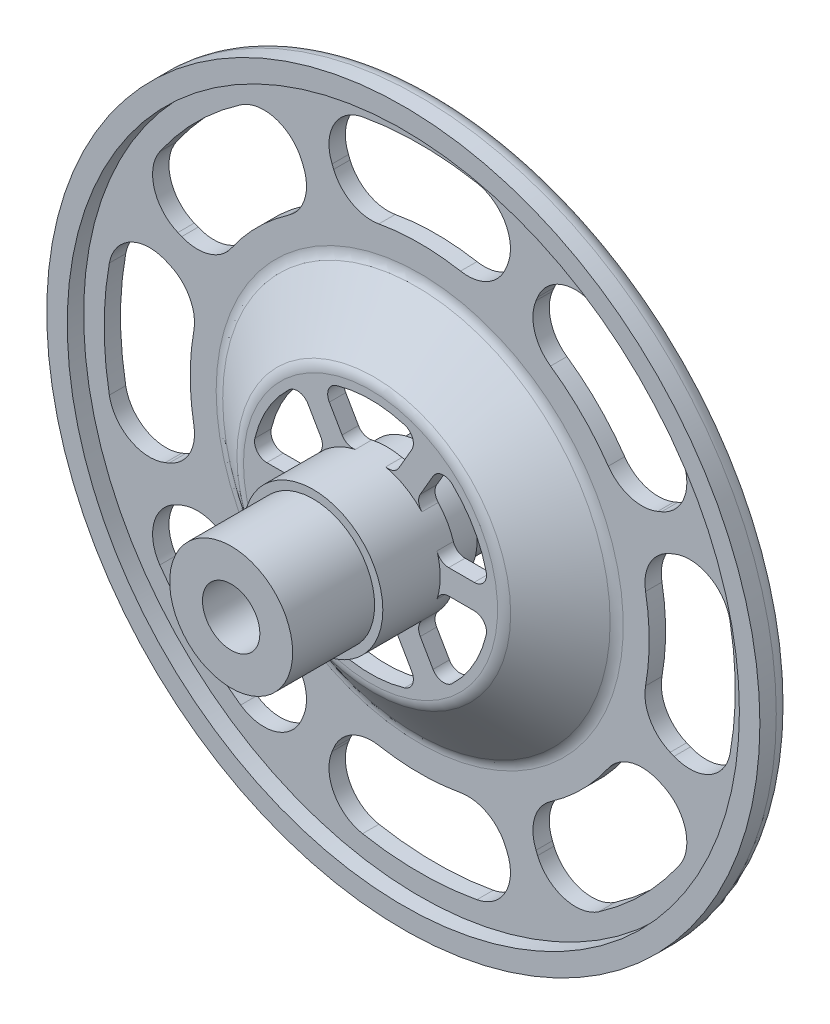
SolidWorks part; units mm, degrees
material "6063-T6"
ref_plane "Front Plane" through (0, 0, 0) normal (0, 0, 1) x (1, 0, 0)
ref_plane "Top Plane" through (0, 0, 0) normal (0, 1, 0) x (1, 0, 0)
ref_plane "Right Plane" through (0, 0, 0) normal (1, 0, 0) x (0, 0, -1)
ref_axis "Axis1" through (0, 0, 54.5094) along (0, 0, -1)
sketch "Sketch2" plane through (0, 0, 0) normal (1, 0, 0) x (0, 0, -1)
  line L0 (0, 3.5) -> (0, 7.5)
  line L1 (17, 8.5) -> (10, 8.5)
  line L3 (17, 16.1667) -> (23, 24.1667)
  line L4 (23, 24.1667) -> (23, 41)
  line L6 (21, 41) -> (21, 43.5)
  line L7 (21, 43.5) -> (25, 43.5)
  line L8 (25, 43.5) -> (25, 23.5)
  line L9 (25, 23.5) -> (19, 15.5)
  line L12 (55, 0) -> (-55, 0) construction
  line L13 (30, 0) -> (23, 0)
  line L14 (17, 16.1667) -> (17, 8.5)
  line L15 (10, 7.5) -> (0, 7.5)
  line L16 (19, 15.5) -> (19, 7)
  line L18 (30, 6) -> (30, 0)
  line L20 (19, 7) -> (23, 7)
  line L21 (23, 7) -> (23, 6)
  line L22 (23, 6) -> (30, 6)
  line L23 (0, 3.5) -> (8, 3.5)
  line L24 (8, 3.5) -> (8, 2.5)
  line L25 (8, 2.5) -> (23, 2.5)
  line L26 (23, 2.5) -> (23, 0)
  line L29 (0, 44.2539) -> (0, -44.2539) construction
  line L30 (21, 41) -> (23, 41)
  line L31 (10, 8.5) -> (10, 7.5)
  line L32 (-54.5094, 0) -> (55.4906, 0) construction
  dimension "D1" = 43.5
  dimension "D2" = 2.5
  dimension "D3" = 2
  dimension "D4" = 2
  dimension "D5" = 15.5
  dimension "D6" = 20
  dimension "D7" = 7
  dimension "D8" = 7.5
  dimension "D9" = 8.5
  dimension "D10" = 7
  dimension "D11" = 6
  dimension "D12" = 4
  dimension "D13" = 7
  dimension "D14" = 4
  dimension "D15" = 30
  dimension "D16" = 6
  dimension "D17" = 2
  dimension "D18" = 3.5
  dimension "D19" = 2.5
  dimension "D20" = 8
revolve "Revolve1" add sketch "Sketch2" angle 360 about axis through (0, 0, 54.5094) along (0, 0, -1)
fillet "Fillet1" radius 2 5 edges at (15.5, 0, -19) (23.5, 0, -25) (16.1667, 0, -17) (24.1667, 0, -23) (43.5, 0, -25)
chamfer "Chamfer1" distance 1.5 angle 45 1 edges at (6, 0, -30)
sketch "Sketch3" plane through (0, 0, -25) normal (0, 0, -1) x (-1, 0, 0)
  line L0 (0, 0) -> (-19.597, 47.3114) construction
  line L1 (0, 0) -> (19.597, 47.3114) construction
  line L2 (-10.6891, 31.0321) -> (-10.4934, 30.5596)
  line L3 (10.6891, 31.0321) -> (10.4934, 30.5596)
  line L4 (-19.597, 47.3114) -> (19.597, 47.3114) construction
  line L6 (0, 44.7868) -> (0, -44.7868) construction
  arc A0 (6.9757, 37.8628) -> (-6.9757, 37.8628) centre (0, 0) ccw
  arc A1 (4.984, 27.5529) -> (-4.984, 27.5529) centre (0, 0) ccw
  arc A2 (10.6891, 31.0321) -> (6.9757, 37.8628) centre (6.0697, 32.9455) ccw
  arc A3 (10.4934, 30.5596) -> (4.984, 27.5529) centre (5.874, 32.473) cw
  arc A4 (-10.4934, 30.5596) -> (-4.984, 27.5529) centre (-5.874, 32.473) ccw
  arc A5 (-10.6891, 31.0321) -> (-6.9757, 37.8628) centre (-6.0697, 32.9455) cw
  point P1 (0, 47.3114)
  point P3 (19.597, 47.3114)
  dimension "D1" = 77
  dimension "D2" = 56
  dimension "D6" = 5
  dimension "D3" = 45
  dimension "D4" = 2
  dimension "D5" = 2
extrude "Cut-Extrude1" cut sketch "Sketch3" against normal up to surface (2 mm away) up to face at (-24.8333, 0, -23)
pattern_circular "CirPattern1" count 8 over 360 about axis through (0, 0, 0) along (0, 0, 1) of "Cut-Extrude1"
sketch "Sketch4" plane through (0, 0, -19) normal (0, 0, -1) x (-1, 0, 0)
  line L1 (0, 0) -> (-11.4833, 19.8897) construction
  line L2 (-11.4833, 19.8897) -> (11.4833, 19.8897) construction
  line L3 (0, 44.7868) -> (0, -44.7868) construction
  line L4 (-5.0255, 11.7045) -> (-3.4707, 9.0114)
  line L5 (0, 0) -> (11.4833, 19.8897) construction
  line L6 (5.0255, 11.7045) -> (3.4707, 9.0114)
  circle A0 centre (0, 0) radius 22.9667 construction
  arc A1 (4.1565, 13.8915) -> (-4.1565, 13.8915) centre (0, 0) ccw
  arc A2 (1.8459, 8.2972) -> (-1.8459, 8.2972) centre (0, 0) ccw
  arc A3 (5.0255, 11.7045) -> (4.1565, 13.8915) centre (3.7265, 12.4545) ccw
  arc A4 (3.4707, 9.0114) -> (1.8459, 8.2972) centre (2.1716, 9.7614) cw
  arc A5 (-3.4707, 9.0114) -> (-1.8459, 8.2972) centre (-2.1716, 9.7614) ccw
  arc A6 (-5.0255, 11.7045) -> (-4.1565, 13.8915) centre (-3.7265, 12.4545) cw
  point P7 (0, 19.8897)
  dimension "D2" = 1.5
  dimension "D4" = 14.5
  dimension "D5" = 8.5
  dimension "D6" = 1.5
  dimension "D1" = 60
  dimension "D3" = 1.5
extrude "Cut-Extrude2" cut sketch "Sketch4" against normal up to surface (2 mm away) up to face at (-15.5, 0, -17)
pattern_circular "CirPattern2" count 6 over 360 about axis through (0, 0, 0) along (0, 0, 1) of "Cut-Extrude2"
